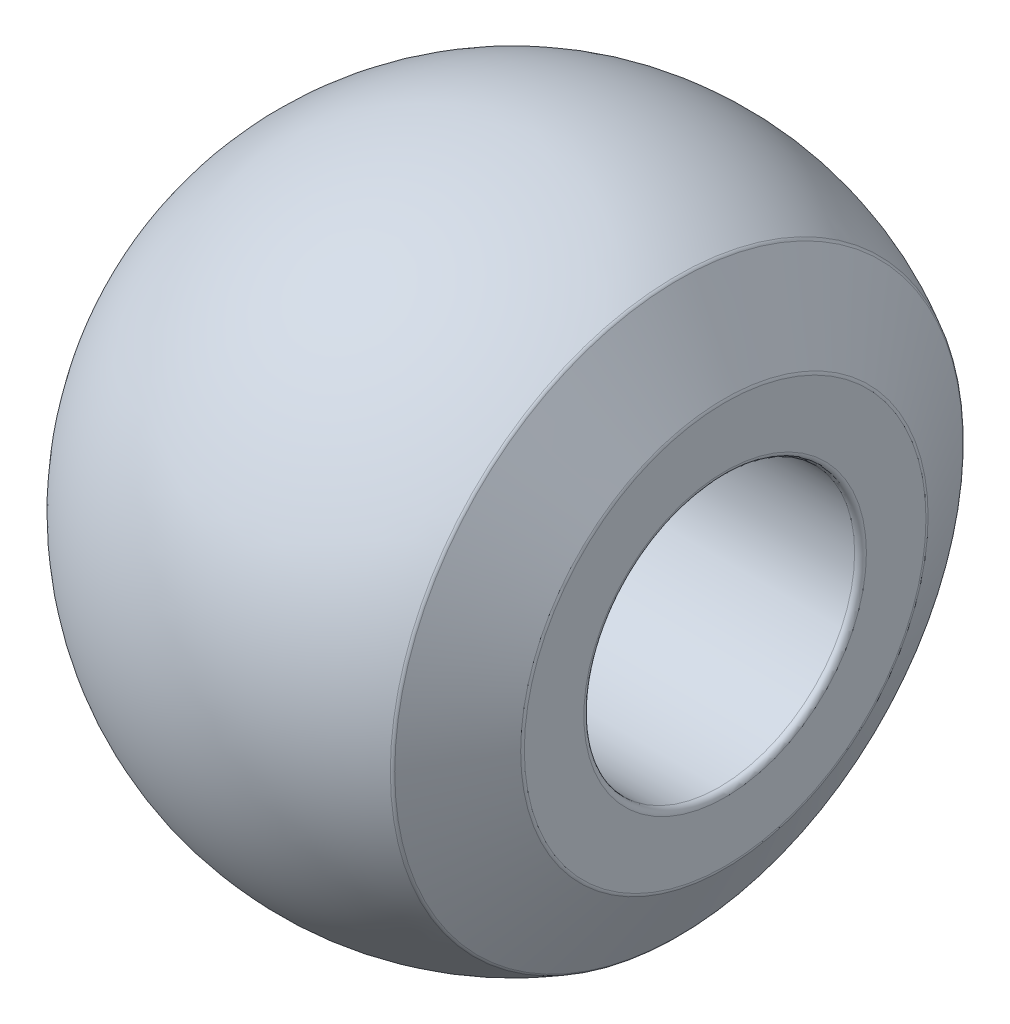
SolidWorks part; units mm, degrees
ref_plane "Front Plane" through (0, 0, 0) normal (0, 0, 1) x (1, 0, 0)
ref_plane "Top Plane" through (0, 0, 0) normal (0, 1, 0) x (1, 0, 0)
ref_plane "Right Plane" through (0, 0, 0) normal (1, 0, 0) x (0, 0, -1)
sketch "Sketch1" plane through (0, 0, 0) normal (0, 1, 0) x (1, 0, 0)
  line L0 (0, 14) -> (0, -14)
  arc A0 (0, 14) -> (0, -14) centre (0, 0) ccw
  dimension "D1" = 28
revolve "Revolve1" add sketch "Sketch1" angle 360 about L0
ref_plane "Plane1" through (9, 0, 0) normal (1, 0, 0) x (0, 0, -1)
sketch "Sketch3" plane through (9, 0, 0) normal (1, 0, 0) x (0, 0, -1)
  circle A0 centre (0, 0) radius 13.805
  dimension "D1" = 27.61
extrude "Cut-Extrude1" cut sketch "Sketch3" along normal blind 10
sketch "Sketch4" plane through (9, 0, 0) normal (1, 0, 0) x (0, 0, -1)
  circle A0 centre (0, 0) radius 5.75
  dimension "D1" = 11.5
extrude "Cut-Extrude2" cut sketch "Sketch4" against normal blind 11
sketch "Sketch6" plane through (0, 0, 0) normal (0, 1, 0) x (1, 0, 0)
  line L0 (7, -12.1244) -> (9.62, -7.5)
  line L1 (9.62, -7.5) -> (9.62, -12.1244)
  line L2 (9.62, -12.1244) -> (7, -12.1244)
  line L4 (0, 0) -> (18.5231, 0) construction
  arc A1 (9, 10.7238) -> (9, -10.7238) centre (0, 0) ccw construction
  dimension "D1" = 9.62
  dimension "D2" = 2.62
  dimension "D3" = 7.5
  dimension "D4" = 12.1244
revolve "Cut-Revolve1" cut sketch "Sketch6" angle 360 about L4
fillet "Fillet1" radius 0.25 3 edges at (7, 0, 12.1244) (9, 0, -8.5943) (9, 0, -5.75)
